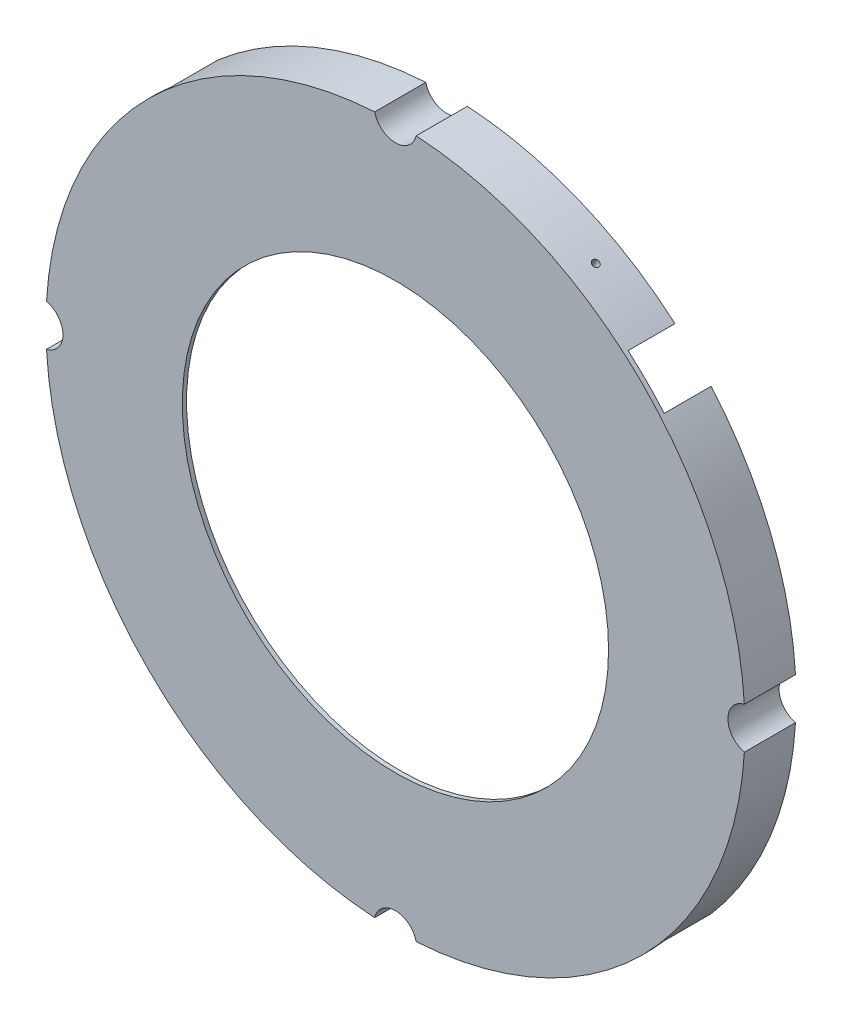
SolidWorks part; units mm, degrees
ref_plane "Front Plane" through (0, 0, 0) normal (0, 0, 1) x (1, 0, 0)
ref_plane "Top Plane" through (0, 0, 0) normal (0, 1, 0) x (1, 0, 0)
ref_plane "Right Plane" through (0, 0, 0) normal (1, 0, 0) x (0, 0, -1)
sketch "Sketch1" plane through (0, 0, 0) normal (0, 0, 1) x (1, 0, 0)
  circle A0 centre (0, 0) radius 50
  circle A1 centre (0, 0) radius 82
extrude "Boss-Extrude1" add sketch "Sketch1" along normal blind 1
sketch "Sketch3" plane through (0, 0, 0) normal (0, 0, -1) x (-1, 0, 0)
  circle A0 centre (0, 0) radius 75
  circle A1 centre (0, 0) radius 82
extrude "Boss-Extrude3" add sketch "Sketch3" along normal blind 11
sketch "Sketch4" plane through (0, 0, 1) normal (0, 0, 1) x (1, 0, 0)
  circle A0 centre (0, 83) radius 5
extrude "Cut-Extrude1" cut sketch "Sketch4" against normal through all
pattern_circular "CirPattern1" count 4 every 90 about axis through (0, 0, 0) along (0, 0, 1) of "Cut-Extrude1"
sketch "Sketch6" plane through (0, 0, -11) normal (0, 0, -1) x (-1, 0, 0)
  line L1 (38.0663, 46.5516) -> (59.4679, 67.9532)
  line L2 (67.8823, 59.397) -> (46.5516, 38.0663)
  line L3 (46.5516, 38.0663) -> (38.0663, 46.5516)
  line L4 (59.4679, 67.9532) -> (67.8823, 59.397)
extrude "Cut-Extrude3" cut sketch "Sketch6" against normal up to surface (11 mm away) up to face at (-75, 0, 0)
pattern_circular "CirPattern3" count 4 every 90 about axis through (0, 0, 0) along (0, 0, 1) of "Cut-Extrude3"
hole_wizard "M2x0.4 Tapped Hole1" positions "3DSketch1" profile "Sketch7" tap size "M2x0.4" standard "ANSI Metric"
sketch3d "3DSketch1"
  point P0 (41, 71.0141, -5)
sketch "Sketch7" plane through (41, 71.0141, -5) normal (0, 0, 1) x (-0.866, 0.5, 0)
  line L0 (0, 0) -> (0, 10.4807)
  line L1 (0, 10.4807) -> (0.8, 10)
  line L2 (0.8, 10) -> (0.8, 0)
  line L5 (0.8, 0) -> (0, 0)
  line L10 (0, 10.4807) -> (-0.8, 10) construction
  line L11 (0, -6.35) -> (0, 107.95) construction
  dimension "Tap Drill Dia." = 1.6
  dimension "Tap Drill Depth" = 10
  dimension "Drill Angle" = 118
